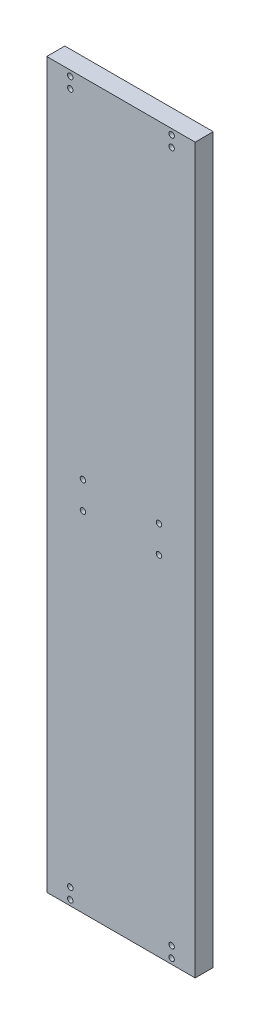
SolidWorks part; units mm, degrees
ref_plane "前视基准面" through (0, 0, 0) normal (0, 0, 1) x (1, 0, 0)
ref_plane "上视基准面" through (0, 0, 0) normal (0, 1, 0) x (1, 0, 0)
ref_plane "右视基准面" through (0, 0, 0) normal (1, 0, 0) x (0, 0, -1)
sketch "草图1" plane through (0, 0, 0) normal (0, 0, 1) x (1, 0, 0)
  line L1 (-41, 200) -> (41, 200)
  line L2 (-41, 200) -> (-41, -200)
  line L3 (-41, -200) -> (41, -200)
  line L4 (41, 200) -> (41, -200)
  line L5 (-41, 200) -> (41, -200) construction
  line L6 (-41, -200) -> (41, 200) construction
  point P0 (0, 0)
  dimension "D1" = 400
  dimension "D2" = 82
extrude "凸台-拉伸1" add sketch "草图1" along normal blind 10
sketch "草图4" plane through (0, 0, 10) normal (0, 0, 1) x (1, 0, 0)
  line L0 (-28, -191) -> (28, -191) construction
  line L1 (28, -191) -> (28, -197) construction
  line L2 (28, -197) -> (-28, -197) construction
  line L3 (-28, -197) -> (-28, -191) construction
  line L4 (-41, -200) -> (41, -200) construction
  line L5 (41, -200) -> (41, 200) construction
  line L6 (-41, 200) -> (-41, -200) construction
  circle A0 centre (28, -197) radius 1.5
  circle A1 centre (28, -191) radius 1.5
  circle A2 centre (-28, -197) radius 1.5
  circle A3 centre (-28, -191) radius 1.5
  dimension "D1" = 3
  dimension "D2" = 3
  dimension "D3" = 3
  dimension "D4" = 3
  dimension "D5" = 3
  dimension "D6" = 6
  dimension "D7" = 13
  dimension "D8" = 13
extrude "切除-拉伸1" cut sketch "草图4" against normal blind 5
mirror "镜向1" about plane through (0, 0, 0) normal (0, 1, 0) of "切除-拉伸1"
sketch "草图5" plane through (0, 0, 10) normal (0, 0, 1) x (1, 0, 0)
  line L0 (-21, 7.5) -> (-21, -7.5) construction
  line L1 (41, 200) -> (-41, 200) construction
  line L2 (-41, 200) -> (-41, -200) construction
  circle A0 centre (-21, 7.5) radius 1.5
  circle A1 centre (-21, -7.5) radius 1.5
  dimension "D3" = 3
  dimension "D4" = 3
  dimension "D1" = 192.5
  dimension "D2" = 20
  dimension "D5" = 15
extrude "切除-拉伸2" cut sketch "草图5" against normal blind 10
mirror "镜向2" about plane through (0, 0, 0) normal (1, 0, 0) of "切除-拉伸2"
